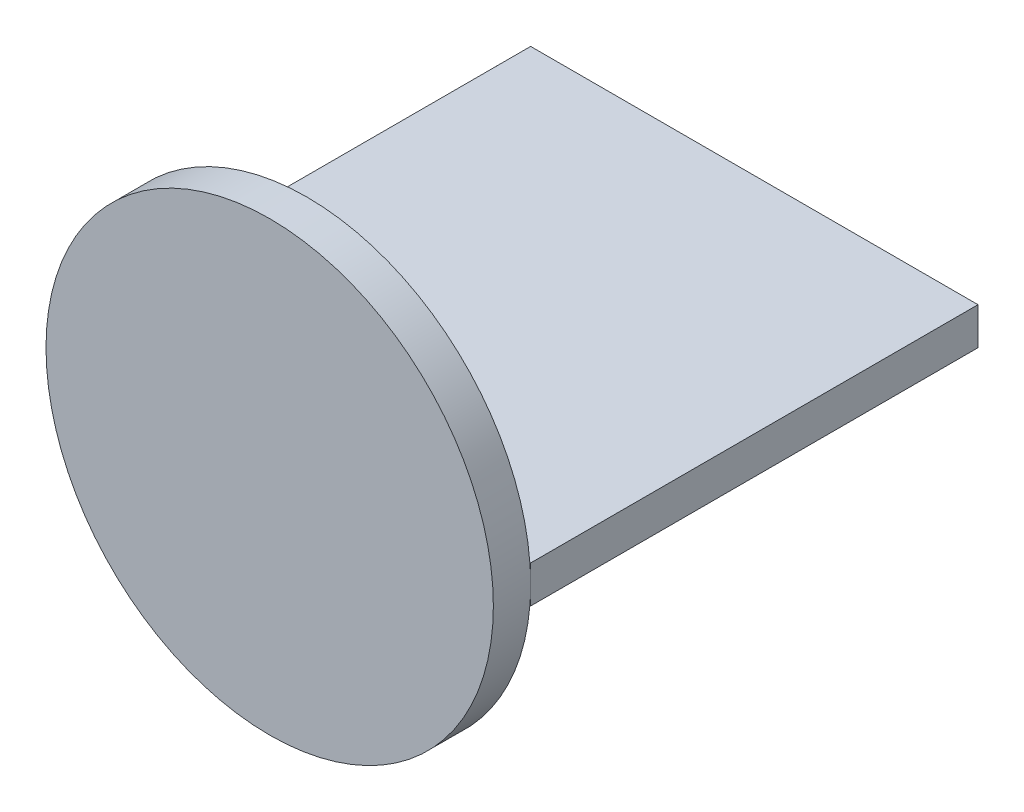
SolidWorks part; units mm, degrees
ref_plane "前视基准面" through (0, 0, 0) normal (0, 0, 1) x (1, 0, 0)
ref_plane "上视基准面" through (0, 0, 0) normal (0, 1, 0) x (1, 0, 0)
ref_plane "右视基准面" through (0, 0, 0) normal (1, 0, 0) x (0, 0, -1)
sketch "草图1" plane through (0, 0, 0) normal (0, 0, 1) x (1, 0, 0)
  circle A0 centre (0, 0) radius 30
  circle A1 centre (0, 0) radius 13.5
  circle A2 centre (0, 13.5) radius 1.8806
  circle A3 centre (11.6913, -6.75) radius 1.8806
  circle A4 centre (-11.6913, -6.75) radius 1.8806
  dimension "D1" = 27
  dimension "D2" = 60
  dimension "D3" = 3
extrude "凸台-拉伸1" add sketch "草图1" along normal blind 10 contours A1 | A0 A1 | A2 | A4 | A3
sketch "草图2" plane through (0, 0, 0) normal (0, 0, -1) x (-1, 0, 0)
  line L1 (-30, -2.5) -> (30, -2.5)
  line L2 (-30, -2.5) -> (-30, 2.5)
  line L7 (-30, 2.5) -> (30, 2.5)
  line L8 (30, -2.5) -> (30, 2.5)
  line L13 (-30, -2.5) -> (30, 2.5) construction
  line L14 (-30, 2.5) -> (30, -2.5) construction
  circle A1 centre (0, 0) radius 25
  point P2 (0, 2.4347)
  dimension "D1" = 5
  dimension "D2" = 60
extrude "凸台-拉伸2" add sketch "草图2" along normal blind 60 contours L7 A1 L1
sketch "草图7" plane through (0, 0, 10) normal (0, 0, 1) x (1, 0, 0)
  circle A0 centre (0, 0) radius 30
extrude "切除-拉伸4" cut sketch "草图7" against normal blind 5
